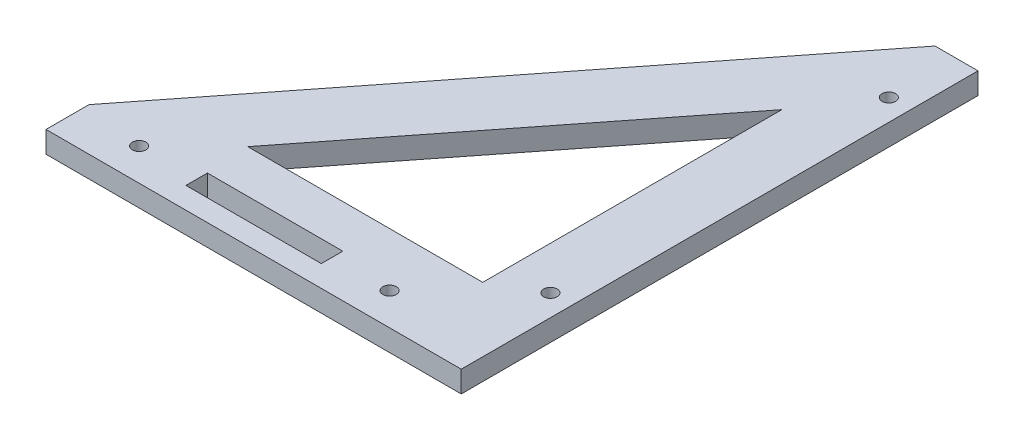
SolidWorks part; units mm, degrees
ref_plane "Front Plane" through (0, 0, 0) normal (0, 0, 1) x (1, 0, 0)
ref_plane "Top Plane" through (0, 0, 0) normal (0, 1, 0) x (1, 0, 0)
ref_plane "Right Plane" through (0, 0, 0) normal (1, 0, 0) x (0, 0, -1)
sketch "Sketch1" plane through (0, 0, 0) normal (0, 1, 0) x (1, 0, 0)
  line L0 (0, 0) -> (55, 0)
  line L1 (55, 0) -> (55, 70)
  line L2 (55, 70) -> (0, 0)
  dimension "D1" = 70
  dimension "D2" = 55
extrude "Boss-Extrude1" add sketch "Sketch1" along normal blind 3.175
sketch "Sketch3" plane through (0, 0, 0) normal (0, -1, 0) x (1, 0, 0)
  line L1 (0, 0) -> (55, 0)
  line L2 (0, 0) -> (0, 6.35)
  line L3 (0, 6.35) -> (55, 6.35)
  line L4 (55, 0) -> (55, 6.35)
  dimension "D1" = 6.35
  dimension "D2" = 55
extrude "Boss-Extrude3" add sketch "Sketch3" against normal blind 3.175
sketch "Sketch5" plane through (0, 0, 0) normal (0, -1, 0) x (1, 0, 0)
  line L1 (55, 6.35) -> (61.35, 6.35)
  line L2 (55, 6.35) -> (55, -70)
  line L3 (55, -70) -> (61.35, -70)
  line L4 (61.35, 6.35) -> (61.35, -70)
  dimension "D1" = 6.35
  dimension "D2" = 76.35
extrude "Boss-Extrude4" add sketch "Sketch5" against normal blind 3.175
sketch "Sketch2" plane through (0, 3.175, 0) normal (0, 1, 0) x (1, 0, 0)
  line L0 (9, -1.5875) -> (46, -1.5875) construction
  line L1 (61.35, 70) -> (61.35, -6.35) construction
  line L2 (17.5, -3.175) -> (37.5, -3.175)
  line L3 (17.5, -3.175) -> (17.5, 0)
  line L4 (17.5, 0) -> (37.5, 0)
  line L5 (37.5, -3.175) -> (37.5, 0)
  line L6 (17.5, -3.175) -> (37.5, 0) construction
  line L7 (17.5, 0) -> (37.5, -3.175) construction
  line L8 (61.35, 70) -> (61.35, -6.35) construction
  line L9 (61.35, -6.35) -> (0, -6.35) construction
  line L12 (61.35, -6.35) -> (0, -6.35) construction
  line L13 (58.175, 33.6763) -> (58.175, -13.6763) construction
  circle A0 centre (9, -1.5875) radius 1
  circle A1 centre (46, -1.5875) radius 1
  circle A2 centre (58.175, 60) radius 1
  circle A3 centre (58.175, 10) radius 1
  point P4 (27.5, -1.5875)
  point P15 (58.175, 10)
  dimension "D2" = 2
  dimension "D3" = 2
  dimension "D4" = 8.5
  dimension "D9" = 2
  dimension "D10" = 2
  dimension "D11" = 16.35
  dimension "D12" = 3.175
  dimension "D1" = 20
  dimension "D5" = 8.5
  dimension "D6" = 4.7625
  dimension "D7" = 3.175
  dimension "D8" = 33.85
  dimension "D13" = 50
extrude "Cut-Extrude1" cut sketch "Sketch2" against normal blind 3.175
sketch "Sketch6" plane through (0, 3.175, 0) normal (0, 1, 0) x (1, 0, 0)
  line L0 (51.825, 6.35) -> (17.1027, 6.35)
  line L1 (17.1027, 6.35) -> (51.825, 50.542)
  line L2 (51.825, 50.542) -> (51.825, 6.35)
  line L3 (61.35, 70) -> (61.35, -6.35) construction
  line L4 (37.5, 0) -> (17.5, 0) construction
  line L6 (55, 70) -> (0, 0) construction
  dimension "D1" = 9.525
  dimension "D2" = 6.35
  dimension "D3" = 9.525
  dimension "D4" = 9.525
extrude "Cut-Extrude2" cut sketch "Sketch6" against normal blind 3.175
